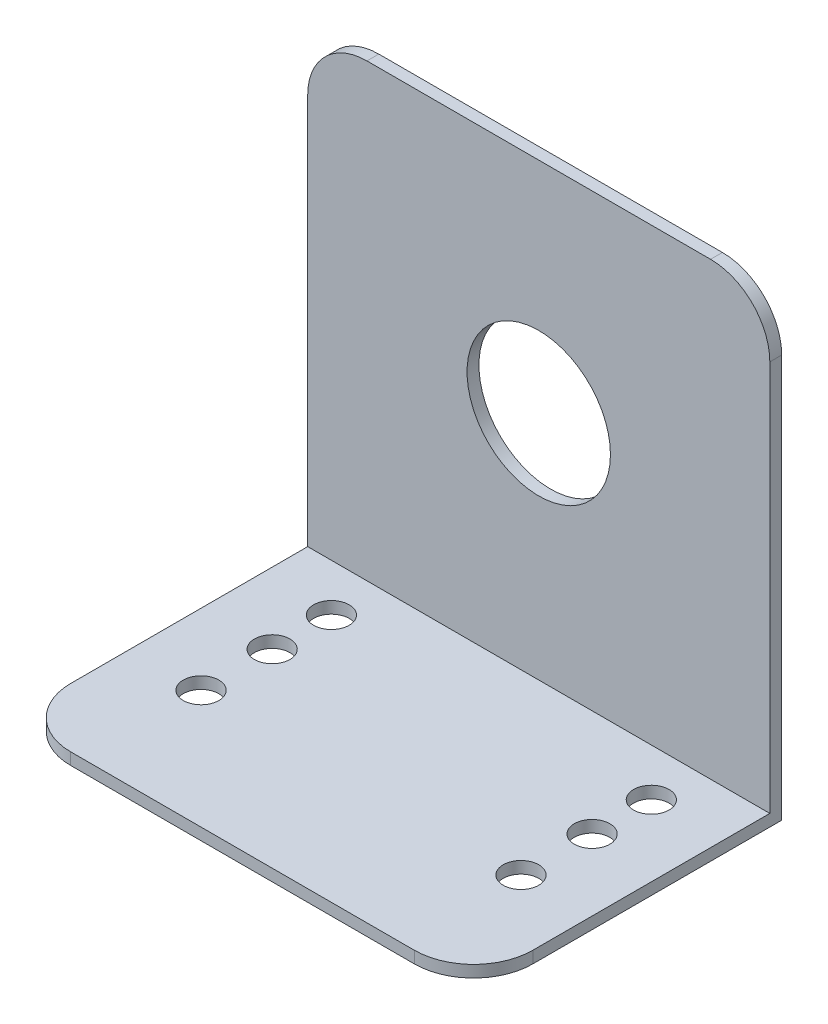
SolidWorks part; units mm, degrees
ref_plane "Front Plane" through (0, 0, 0) normal (0, 0, 1) x (1, 0, 0)
ref_plane "Top Plane" through (0, 0, 0) normal (0, 1, 0) x (1, 0, 0)
ref_plane "Right Plane" through (0, 0, 0) normal (1, 0, 0) x (0, 0, -1)
sketch "Sketch1" plane through (0, 0, 0) normal (0, 0, 1) x (1, 0, 0)
  line L1 (-19.5, -19.5) -> (19.5, -19.5)
  line L2 (-19.5, -19.5) -> (-19.5, 19.5)
  line L3 (-19.5, 19.5) -> (19.5, 19.5)
  line L4 (19.5, -19.5) -> (19.5, 19.5)
  line L5 (-19.5, -19.5) -> (19.5, 19.5) construction
  line L6 (-19.5, 19.5) -> (19.5, -19.5) construction
  point P0 (0, 0)
  dimension "D1" = 39
  dimension "D2" = 39
extrude "Boss-Extrude1" add sketch "Sketch1" along normal blind 1
sketch "Sketch2" plane through (0, 0, 1) normal (0, 0, 1) x (1, 0, 0)
  line L0 (-19.5, -19.5) -> (19.5, -19.5)
  line L1 (19.5, -19.5) -> (19.5, -18.5)
  line L2 (19.5, -19.5) -> (19.5, 19.5) construction
  line L3 (19.5, -18.5) -> (-19.5, -18.5)
  line L4 (-19.5, 19.5) -> (-19.5, -19.5) construction
  line L5 (-19.5, -18.5) -> (-19.5, -19.5)
  dimension "D1" = 1
extrude "Boss-Extrude2" add sketch "Sketch2" along normal blind 25
sketch "Sketch3" plane through (0, 0, 0) normal (0, 0, -1) x (-1, 0, 0)
  point P3 (0, 0)
sketch "Sketch5" plane through (0, -19.5, 0) normal (0, -1, 0) x (1, 0, 0)
  circle A0 centre (13.5, 5) radius 1.5
  circle A1 centre (13.5, 10) radius 1.5
  circle A2 centre (13.5, 16) radius 1.5
  dimension "D2" = 3
  dimension "D3" = 3
  dimension "D4" = 3
  dimension "D6" = 5
  dimension "D7" = 6
extrude "Cut-Extrude2" cut sketch "Sketch5" against normal blind 1
sketch "Sketch6" plane through (0, -19.5, 0) normal (0, -1, 0) x (1, 0, 0)
  circle A0 centre (-13.5, 16) radius 1.5
  circle A1 centre (-13.5, 10) radius 1.5
  circle A2 centre (-13.5, 5) radius 1.5
  dimension "D4" = 3
  dimension "D5" = 3
  dimension "D6" = 3
  dimension "D2" = 5
  dimension "D3" = 6
extrude "Cut-Extrude3" cut sketch "Sketch6" against normal blind 1
fillet "Fillet1" radius 5 4 edges at (-19.5, -19, 26) (19.5, -19, 26) (19.5, 19.5, 0.5) (-19.5, 19.5, 0.5)
sketch "Sketch7" plane through (0, 0, 0) normal (0, 0, 1) x (1, 0, 0)
  circle A0 centre (0, 1) radius 6.05
  dimension "D1" = 12.1
  dimension "D2" = 1
extrude "Cut-Extrude4" cut sketch "Sketch7" along normal blind 1
